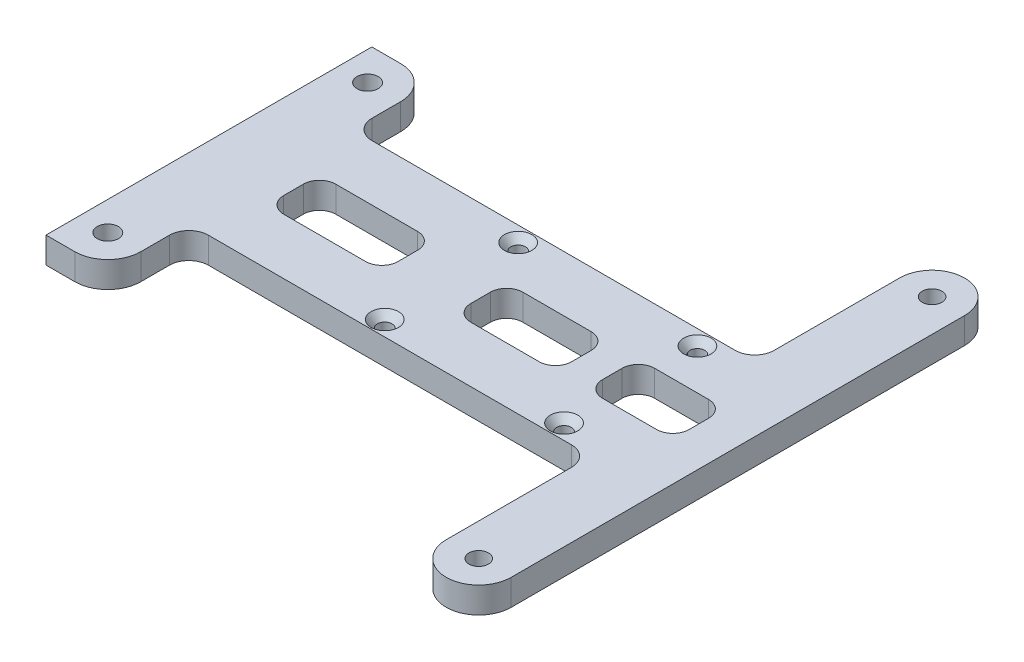
SolidWorks part; units mm, degrees
ref_plane "Alzado" through (0, 0, 0) normal (0, 0, 1) x (1, 0, 0)
ref_plane "Planta" through (0, 0, 0) normal (0, 1, 0) x (1, 0, 0)
ref_plane "Vista lateral" through (0, 0, 0) normal (1, 0, 0) x (0, 0, -1)
sketch "Croquis1" plane through (0, 0, 0) normal (0, 1, 0) x (1, 0, 0)
  line L0 (0, -50.075) -> (0, 50.075)
  line L1 (0, 50.075) -> (8.85, 50.075)
  line L2 (19, 39.925) -> (19, 31.15)
  line L3 (25, 25.15) -> (136.6, 25.15)
  line L4 (142.6, 31.15) -> (142.6, 69.675)
  line L5 (162.6, 69.675) -> (162.6, -69.675)
  line L6 (0, -50.075) -> (8.85, -50.075)
  line L7 (19, -39.925) -> (19, -31.15)
  line L8 (25, -25.15) -> (136.6, -25.15)
  line L9 (142.6, -31.15) -> (142.6, -69.675)
  line L10 (124, -8) -> (150.6, -8)
  line L11 (124, -8) -> (124, 8)
  line L12 (150.6, -8) -> (150.6, 8)
  line L13 (124, 8) -> (150.6, 8)
  line L14 (124, -8) -> (150.6, 8) construction
  line L15 (150.6, -8) -> (124, 8) construction
  line L16 (83.5, -8) -> (114.5, -8)
  line L17 (83.5, -8) -> (83.5, 8)
  line L18 (114.5, -8) -> (114.5, 8)
  line L19 (83.5, 8) -> (114.5, 8)
  line L20 (83.5, -8) -> (114.5, 8) construction
  line L21 (114.5, -8) -> (83.5, 8) construction
  line L22 (26, -8) -> (61.15, -8)
  line L23 (26, -8) -> (26, 8)
  line L24 (61.15, -8) -> (61.15, 8)
  line L25 (26, 8) -> (61.15, 8)
  line L26 (26, -8) -> (61.15, 8) construction
  line L27 (61.15, -8) -> (26, 8) construction
  line L28 (-55, 0) -> (55, 0) construction
  arc A0 (142.6, 69.675) -> (162.6, 69.675) centre (152.6, 69.675) cw
  arc A1 (162.6, -69.675) -> (142.6, -69.675) centre (152.6, -69.675) cw
  circle A2 centre (152.6, 69.675) radius 3
  circle A3 centre (152.6, -69.675) radius 3
  circle A4 centre (8.85, 39.925) radius 3.25
  arc A5 (8.85, 50.075) -> (19, 39.925) centre (8.85, 39.925) cw
  circle A6 centre (8.85, -39.925) radius 3.25
  arc A7 (8.85, -50.075) -> (19, -39.925) centre (8.85, -39.925) ccw
  arc A8 (136.6, 25.15) -> (142.6, 31.15) centre (136.6, 31.15) ccw
  arc A9 (136.6, -25.15) -> (142.6, -31.15) centre (136.6, -31.15) cw
  arc A10 (19, -31.15) -> (25, -25.15) centre (25, -31.15) cw
  arc A11 (19, 31.15) -> (25, 25.15) centre (25, 31.15) ccw
  point P4 (0, 0)
  point P19 (99, 0)
  point P20 (43.575, 0)
  point P21 (137.3, 0)
  point P23 (162.6, 0)
  point P48 (142.6, 25.15)
  point P51 (142.6, -25.15)
  point P54 (19, -25.15)
  point P57 (19, 25.15)
  dimension "D5" = 6
  dimension "D6" = 6
  dimension "D17" = 6.5
  dimension "D18" = 10.15
  dimension "D20" = 10.15
  dimension "D21" = 10.15
  dimension "D22" = 6
  dimension "D1" = 139.35
  dimension "D2" = 123.6
  dimension "D3" = 20
  dimension "D4" = 162.6
  dimension "D7" = 50.3
  dimension "D8" = 25.15
  dimension "D9" = 100.15
  dimension "D10" = 16
  dimension "D11" = 12
  dimension "D12" = 9.5
  dimension "D13" = 22.35
  dimension "D14" = 35.15
  dimension "D15" = 26
  dimension "D16" = 31
  dimension "D19" = 10.15
extrude "Saliente-Extruir1" add sketch "Croquis1" along normal blind 8
fillet "Redondeo3" radius 5 12 edges at (124, 4, 8) (150.6, 4, 8) (124, 4, -8) (150.6, 4, -8) (83.5, 4, 8) (114.5, 4, 8) (114.5, 4, -8) (83.5, 4, -8) (26, 4, 8) (61.15, 4, 8) (61.15, 4, -8) (26, 4, -8)
sketch "Croquis2" plane through (0, 8, 0) normal (0, 1, 0) x (1, 0, 0)
  line L0 (162.6, -69.675) -> (162.6, 69.675) construction
  line L1 (25, -25.15) -> (136.6, -25.15) construction
  line L2 (-4.4, 0) -> (4.4, 0) construction
  circle A0 centre (129.65, -20.5) radius 2.15
  circle A1 centre (74.55, -20.5) radius 2.15
  circle A2 centre (129.65, 20.5) radius 2.15
  circle A3 centre (74.55, 20.5) radius 2.15
  point P8 (0, 0)
  dimension "D1" = 4.3
  dimension "D2" = 32.95
  dimension "D3" = 4.65
  dimension "D4" = 55.1
hole_wizard "Avellanado para tornillo con cabeza ovalada de #81" positions "Croquis3" profile "Croquis4" countersink size "#8" standard "Ansi Inch" end condition through all
sketch "Croquis3" plane through (0, 8, 0) normal (0, 1, 0) x (1, 0, 0)
  point P0 (74.55, 20.5)
  point P3 (129.65, 20.5)
  point P6 (74.55, -20.5)
  point P9 (129.65, -20.5)
sketch "Croquis4" plane through (74.55, 8, -20.5) normal (1, 0, 0) x (0, 0, 1)
  line L0 (0, 0) -> (0, 8)
  line L1 (0, 8) -> (2.2479, 8)
  line L2 (2.2479, 8) -> (2.2479, 2.2645)
  line L3 (2.2479, 2.2645) -> (4.2164, 0)
  line L5 (4.2164, 0) -> (0, 0)
  line L6 (-2.2479, 2.2645) -> (-4.2164, 0) construction
  line L11 (0, -6.35) -> (0, 107.95) construction
  dimension "Diámetro de taladro hasta el siguiente" = 4.4958
  dimension "Profundidad de taladro hasta el siguiente" = 8
  dimension "Diámetro de avellanado cercano" = 8.4328
  dimension "Ángulo de avellanado cercano" = 82
